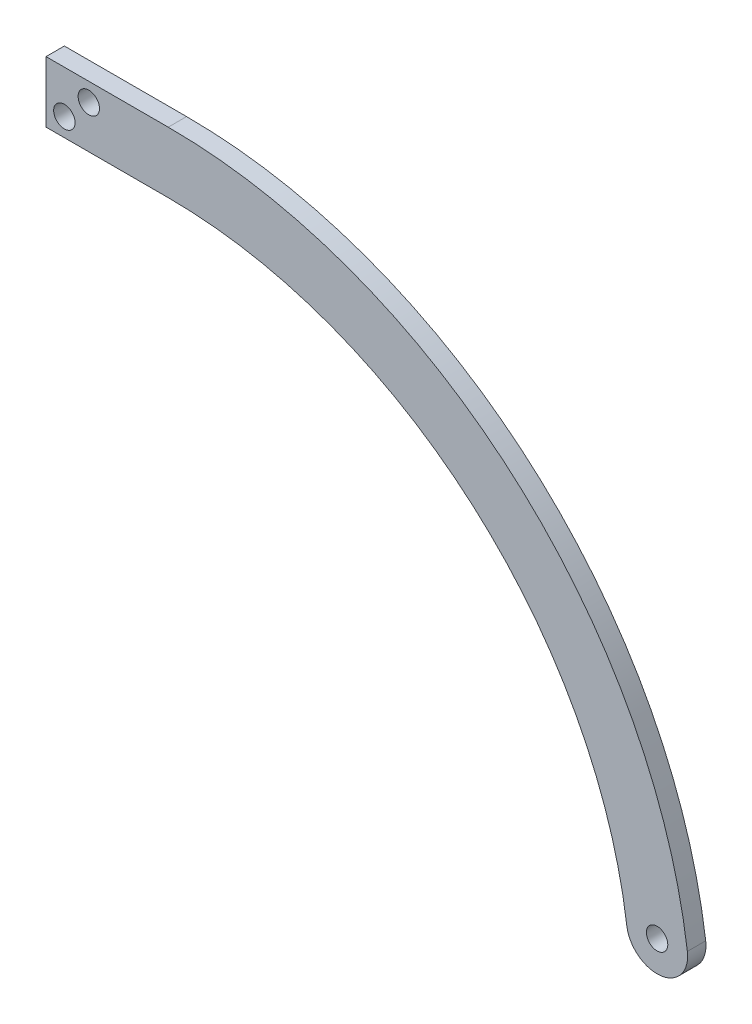
SolidWorks part; units mm, degrees
ref_plane "Plano frontal" through (0, 0, 0) normal (0, 0, 1) x (1, 0, 0)
ref_plane "Plano superior" through (0, 0, 0) normal (0, 1, 0) x (1, 0, 0)
ref_plane "Plano direito" through (0, 0, 0) normal (1, 0, 0) x (0, 0, -1)
sketch "Esboço1" plane through (0, 0, 0) normal (0, 0, 1) x (1, 0, 0)
  line L1 (-20, 5) -> (0, 5)
  line L2 (-20, 5) -> (-20, -5)
  line L3 (-20, -5) -> (0, -5)
  line L4 (0, 5) -> (0, -5)
  circle A0 centre (-13, 2) radius 1.75
  circle A1 centre (-17, -2) radius 1.75
  arc A2 (0, 0) -> (80, -70) centre (0, -80.7143) cw construction
  arc A3 (84.9558, -69.3363) -> (0, 5) centre (0, -80.7143) ccw
  arc A4 (75.0442, -70.6637) -> (0, -5) centre (0, -80.7143) ccw
  arc A5 (75.0442, -70.6637) -> (84.9558, -69.3363) centre (80, -70) ccw
  arc A6 (0, 5) -> (0, -5) centre (0, 0) ccw
  circle A7 centre (80, -70) radius 1.75
  point P11 (53.1507, -19.9706)
  dimension "D1" = 3.5
  dimension "D10" = 3.5
  dimension "D2" = 10
  dimension "D3" = 7
  dimension "D4" = 3
  dimension "D5" = 3
  dimension "D6" = 3
  dimension "D7" = 20
  dimension "D8" = 100
  dimension "D9" = 70
extrude "Ressalto-extrusão1" add sketch "Esboço1" along normal blind 3 contours A6 L1 L2 L3 A1 A0 | A4 A5 A3 L4 A7 | L4 A6
